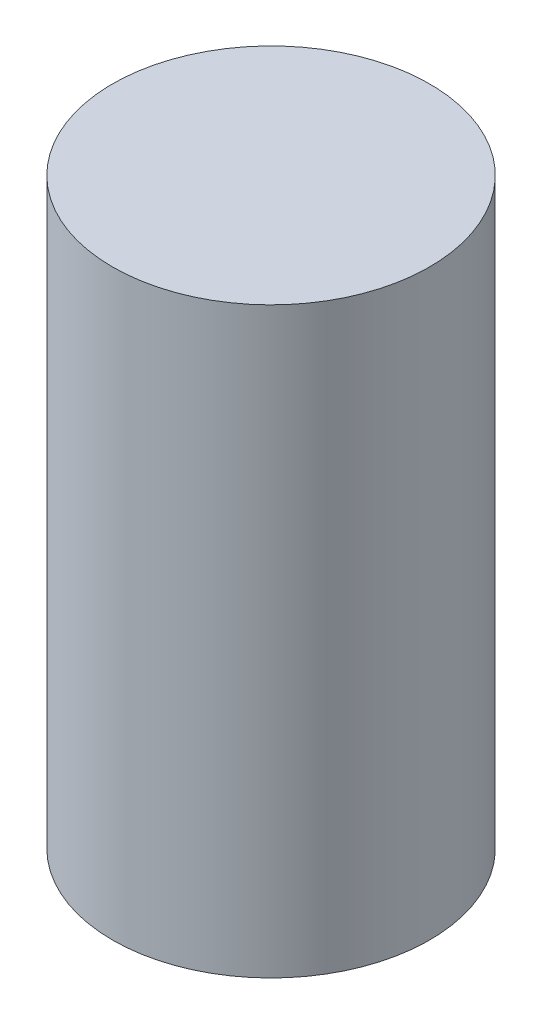
SolidWorks part; units mm, degrees
ref_plane "Front Plane" through (0, 0, 0) normal (0, 0, 1) x (1, 0, 0)
ref_plane "Top Plane" through (0, 0, 0) normal (0, 1, 0) x (1, 0, 0)
ref_plane "Right Plane" through (0, 0, 0) normal (1, 0, 0) x (0, 0, -1)
sketch "Sketch2" plane through (0, 0, 0) normal (0, 1, 0) x (1, 0, 0)
  circle A0 centre (0, 0) radius 68
  dimension "D1" = 136
extrude "Boss-Extrude3" add sketch "Sketch2" along normal blind 250 contours A0
